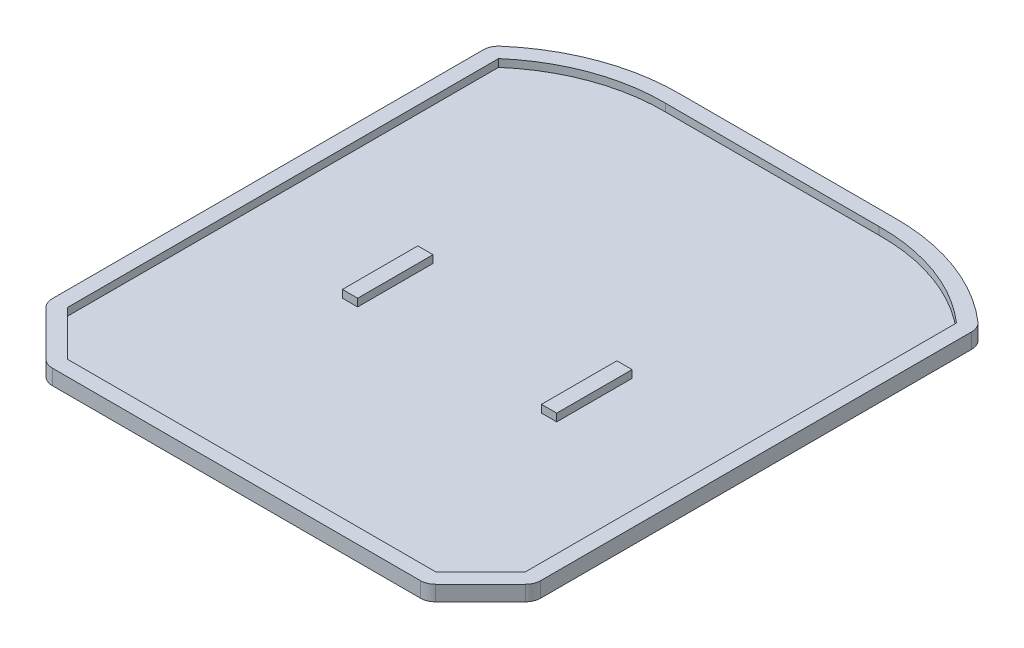
SolidWorks part; units mm, degrees
ref_plane "Front Plane" through (0, 0, 0) normal (0, 0, 1) x (1, 0, 0)
ref_plane "Top Plane" through (0, 0, 0) normal (0, 1, 0) x (1, 0, 0)
ref_plane "Right Plane" through (0, 0, 0) normal (1, 0, 0) x (0, 0, -1)
sketch "Sketch1" plane through (0, 0, 0) normal (0, 1, 0) x (1, 0, 0)
  line L0 (0, 0) -> (250, 0)
  line L2 (285.3553, 35.3553) -> (285.3553, 326.9553)
  line L6 (-35.3553, 326.9553) -> (-35.3553, 35.3553)
  line L9 (285.3553, 35.3553) -> (250, 0)
  line L10 (0, 0) -> (-35.3553, 35.3553)
  line L11 (55, 361.9553) -> (195, 361.9553)
  arc A0 (-35.3553, 326.9553) -> (55, 361.9553) centre (53.3964, 231.9652) cw
  arc A1 (285.3553, 326.9553) -> (195, 361.9553) centre (196.6036, 231.9652) ccw
  point P8 (125, 0)
  point P10 (125, 361.9553)
  dimension "D12" = 130
  dimension "D11" = 130
  dimension "D1" = 250
  dimension "D2" = 50
  dimension "D3" = 135
  dimension "D4" = 135
  dimension "D5" = 50
  dimension "D6" = 135
  dimension "D7" = 135
  dimension "D8" = 291.6
  dimension "D9" = 291.6
  dimension "D10" = 140
extrude "Body" add sketch "Sketch1" along normal blind 10 contours A0 L11 A1 L2 L9 L0 L10 L6
sketch "Sketch2" plane through (0, 10, 0) normal (0, 1, 0) x (1, 0, 0)
  line L0 (-25.3553, 322.5089) -> (-25.3553, 39.4975)
  line L1 (-25.3553, 39.4975) -> (4.1421, 10)
  line L2 (4.1421, 10) -> (245.8579, 10)
  line L3 (245.8579, 10) -> (275.3553, 39.4975)
  line L4 (275.3553, 39.4975) -> (275.3553, 322.5089)
  line L5 (195.0629, 351.9553) -> (54.9371, 351.9553)
  line L6 (-35.3553, 326.9553) -> (-35.3553, 35.3553)
  line L7 (195, 361.9553) -> (55, 361.9553)
  line L8 (285.3553, 35.3553) -> (285.3553, 326.9553)
  line L9 (250, 0) -> (285.3553, 35.3553)
  line L10 (0, 0) -> (250, 0)
  line L11 (-35.3553, 35.3553) -> (0, 0)
  line L12 (-35.3553, 326.9553) -> (-35.3553, 35.3553)
  line L13 (195, 361.9553) -> (55, 361.9553)
  line L14 (285.3553, 35.3553) -> (285.3553, 326.9553)
  line L15 (250, 0) -> (285.3553, 35.3553)
  line L16 (0, 0) -> (250, 0)
  line L17 (-35.3553, 35.3553) -> (0, 0)
  arc A0 (275.3553, 322.5089) -> (195.0629, 351.9553) centre (196.6036, 231.9652) ccw
  arc A1 (54.9371, 351.9553) -> (-25.3553, 322.5089) centre (53.3964, 231.9652) ccw
  arc A2 (55, 361.9553) -> (-35.3553, 326.9553) centre (53.3964, 231.9652) ccw
  arc A3 (285.3553, 326.9553) -> (195, 361.9553) centre (196.6036, 231.9652) ccw
  arc A4 (55, 361.9553) -> (-35.3553, 326.9553) centre (53.3964, 231.9652) ccw
  arc A5 (285.3553, 326.9553) -> (195, 361.9553) centre (196.6036, 231.9652) ccw
  dimension "D1" = 0
  dimension "D2" = 10
extrude "Inside Body" cut sketch "Sketch2" against normal blind 5 contours L0 L1 L2 L3 L4 A0 L5 A1
sketch "Sketch3" plane through (0, 5, 0) normal (0, 1, 0) x (1, 0, 0)
  line L1 (54.6447, 189.5) -> (64.6447, 189.5)
  line L2 (54.6447, 189.5) -> (54.6447, 140)
  line L3 (54.6447, 140) -> (64.6447, 140)
  line L4 (64.6447, 189.5) -> (64.6447, 140)
  line L6 (195.0629, 351.9553) -> (54.9371, 351.9553) construction
  line L7 (125, 351.9553) -> (125, 112.7156) construction
  line L8 (195.3553, 140) -> (185.3553, 140)
  line L9 (185.3553, 189.5) -> (185.3553, 140)
  line L10 (195.3553, 189.5) -> (185.3553, 189.5)
  line L11 (195.3553, 189.5) -> (195.3553, 140)
  line L16 (-25.3553, 322.5089) -> (-25.3553, 39.4975)
  line L18 (-25.3553, 322.5089) -> (-25.3553, 39.4975)
  line L20 (-25.3553, 39.4975) -> (4.1421, 10)
  line L22 (-25.3553, 39.4975) -> (4.1421, 10)
  line L30 (4.1421, 10) -> (245.8579, 10)
  line L32 (4.1421, 10) -> (245.8579, 10)
  line L34 (245.8579, 10) -> (275.3553, 39.4975)
  line L35 (245.8579, 10) -> (275.3553, 39.4975)
  line L36 (275.3553, 39.4975) -> (275.3553, 322.5089)
  line L37 (275.3553, 39.4975) -> (275.3553, 322.5089)
  line L38 (195.0629, 351.9553) -> (54.9371, 351.9553)
  line L39 (195.0629, 351.9553) -> (54.9371, 351.9553)
  arc A2 (54.9371, 351.9553) -> (-25.3553, 322.5089) centre (53.3964, 231.9652) ccw
  arc A6 (54.9371, 351.9553) -> (-25.3553, 322.5089) centre (53.3964, 231.9652) ccw
  arc A8 (275.3553, 322.5089) -> (195.0629, 351.9553) centre (196.6036, 231.9652) ccw
  arc A9 (275.3553, 322.5089) -> (195.0629, 351.9553) centre (196.6036, 231.9652) ccw
  dimension "D1" = 10
  dimension "D2" = 49.5
  dimension "D4" = 0
extrude "Horizontal Constraints" add sketch "Sketch3" along normal blind 5 contours L9 L8 L11 L10 | L4 L3 L2 L1
fillet "Fillet1" radius 10 6 edges at (-35.3553, 5, -326.9553) (285.3553, 5, -326.9553) (285.3553, 5, -35.3553) (250, 5, 0) (0, 5, 0) (-35.3553, 5, -35.3553)
sketch "Sketch5" plane through (0, 0, 0) normal (0, -1, 0) x (1, 0, 0)
  line L0 (-35.3553, -322.5089) -> (-35.3553, -39.4975) construction
  line L1 (145, -231.0032) -> (105, -231.0032)
  line L2 (145, -231.0032) -> (145, -131.0032)
  line L3 (145, -131.0032) -> (105, -131.0032)
  line L4 (105, -231.0032) -> (105, -131.0032)
  line L11 (-25.3553, -39.4975) -> (-25.3553, -322.5089)
  line L12 (4.1421, -10) -> (-25.3553, -39.4975)
  line L13 (245.8579, -10) -> (4.1421, -10)
  line L14 (275.3553, -39.4975) -> (245.8579, -10)
  line L15 (275.3553, -322.5089) -> (275.3553, -39.4975)
  line L16 (54.9371, -351.9553) -> (195.0629, -351.9553)
  line L17 (-25.3553, -39.4975) -> (-25.3553, -322.5089)
  line L18 (4.1421, -10) -> (-25.3553, -39.4975)
  line L19 (245.8579, -10) -> (4.1421, -10)
  line L20 (275.3553, -39.4975) -> (245.8579, -10)
  line L21 (275.3553, -322.5089) -> (275.3553, -39.4975)
  line L22 (54.9371, -351.9553) -> (195.0629, -351.9553)
  arc A2 (-25.3553, -322.5089) -> (54.9371, -351.9553) centre (53.3964, -231.9652) ccw
  arc A3 (195.0629, -351.9553) -> (275.3553, -322.5089) centre (196.6036, -231.9652) ccw
  arc A4 (-25.3553, -322.5089) -> (54.9371, -351.9553) centre (53.3964, -231.9652) ccw
  arc A5 (195.0629, -351.9553) -> (275.3553, -322.5089) centre (196.6036, -231.9652) ccw
  point P6 (125, -231.0032)
  point P13 (125, -351.9553)
  point P15 (145, -181.0032)
  point P17 (275.3553, -181.0032)
  dimension "D2" = 40
  dimension "D3" = 100
  dimension "D1" = 0
